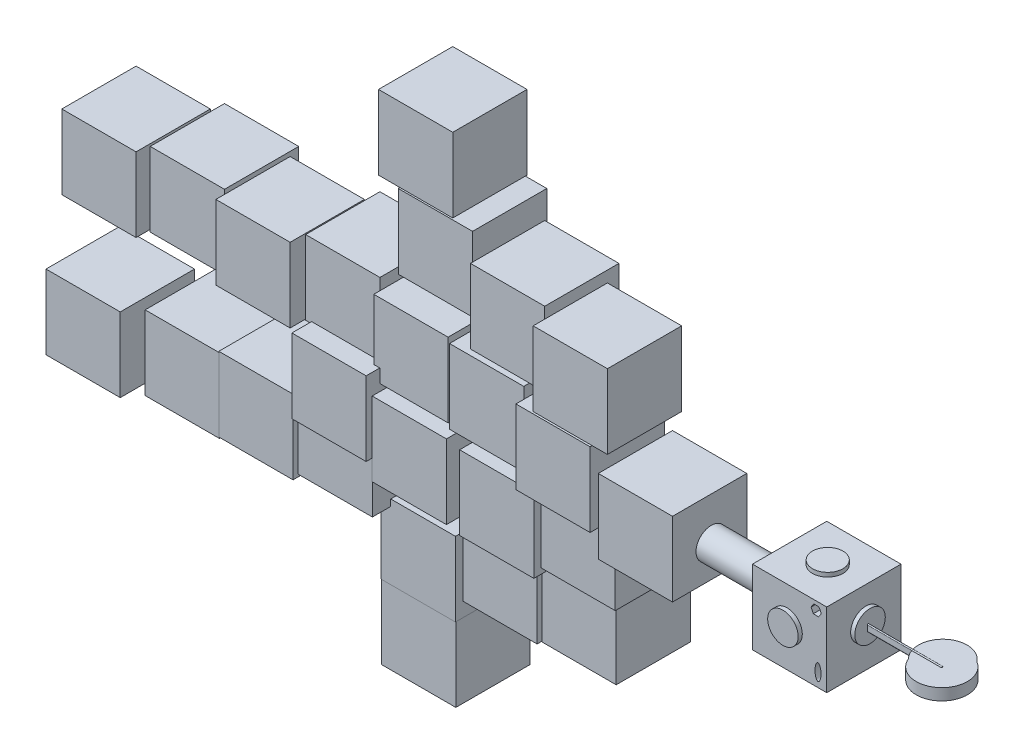
SolidWorks part; units mm, degrees
ref_plane "Front Plane" through (0, 0, 0) normal (0, 0, 1) x (1, 0, 0)
ref_plane "Top Plane" through (0, 0, 0) normal (0, 1, 0) x (1, 0, 0)
ref_plane "Right Plane" through (0, 0, 0) normal (1, 0, 0) x (0, 0, -1)
sketch "Sketch1" plane through (0, 0, 0) normal (0, 0, 1) x (1, 0, 0)
  line L1 (-45, 45) -> (45, 45)
  line L2 (-45, 45) -> (-45, -45)
  line L3 (-45, -45) -> (45, -45)
  line L4 (45, 45) -> (45, -45)
  line L5 (-45, 45) -> (45, -45) construction
  line L6 (-45, -45) -> (45, 45) construction
  point P0 (0, 0)
  dimension "D1" = 90
  dimension "D2" = 90
extrude "Boss-Extrude1" add sketch "Sketch1" along normal blind 90
sketch "Sketch2" plane through (45, 0, 0) normal (1, 0, 0) x (0, 0, -1)
  circle A0 centre (-42.5335, 3.7359) radius 18.4951
extrude "Boss-Extrude2" add sketch "Sketch2" against normal blind 90 and the other way blind 5
sketch "Sketch3" plane through (0, 0, 90) normal (0, 0, 1) x (1, 0, 0)
  circle A0 centre (-3.1268, 1.6243) radius 18.4951
extrude "Boss-Extrude3" add sketch "Sketch3" against normal blind 90 and the other way blind 5
sketch "Sketch4" plane through (0, 45, 0) normal (0, 1, 0) x (0, 0, -1)
  circle A0 centre (-44.963, -1.1407) radius 18.4951
extrude "Boss-Extrude4" add sketch "Sketch4" against normal blind 90 and the other way blind 5
sketch "Sketch5" plane through (-45, 0, 0) normal (-1, 0, 0) x (0, 0, 1)
  circle A0 centre (44.3232, -3.4807) radius 18.4951
extrude "Boss-Extrude5" add sketch "Sketch5" against normal blind 90 and the other way blind 95.6719
sketch "Sketch6" plane through (0, -45, 0) normal (0, -1, 0) x (0, 0, -1)
  circle A0 centre (-43.114, -1.0732) radius 18.4951
extrude "Boss-Extrude6" add sketch "Sketch6" against normal blind 90 and the other way blind 5
sketch "Sketch7" plane through (0, 0, 0) normal (0, 0, -1) x (-1, 0, 0)
  line L1 (-28.8022, 29.8056) -> (-25.9491, 35.3523)
  line L2 (-25.9491, 35.3523) -> (-29.3261, 40.5965)
  line L3 (-29.3261, 40.5965) -> (-35.5562, 40.294)
  line L4 (-35.5562, 40.294) -> (-38.4093, 34.7474)
  line L5 (-38.4093, 34.7474) -> (-35.0323, 29.5031)
  line L6 (-35.0323, 29.5031) -> (-28.8022, 29.8056)
  circle A0 centre (-32.1792, 35.0498) radius 5.4018 construction
extrude "Cut-Extrude1" cut sketch "Sketch7" against normal blind 90
sketch "Sketch8" plane through (0, 0, 90) normal (0, 0, 1) x (1, 0, 0)
  ellipse E0 centre (34.4176, -28.6824) end of major axis (34.4176, -38.4588) minor radius 3.6403
extrude "Cut-Extrude2" cut sketch "Sketch8" against normal blind 90
sketch "Sketch9" plane through (50, 0, 0) normal (1, 0, 0) x (0, 0, -1)
  line L0 (-44.9872, 6.623) -> (-44.9872, 0) construction
  line L1 (-44.0735, 6.623) -> (-44.0735, 0)
  line L2 (-45.9008, 6.623) -> (-45.9008, 0)
  arc A0 (-44.0735, 6.623) -> (-45.9008, 6.623) centre (-44.9872, 6.623) ccw
  arc A1 (-45.9008, 0) -> (-44.0735, 0) centre (-44.9872, 0) ccw
  point P2 (-44.9872, 3.3115)
extrude "Boss-Extrude7" add sketch "Sketch9" along normal blind 90
ref_plane "Plane1" through (140, 6.623, 44.0735) normal (0, 1, 0) x (1, 0, 0)
sketch "Sketch10" plane through (140, 6.623, 44.0735) normal (0, 1, 0) x (1, 0, 0)
  circle A0 centre (-8.4258, 8.1881) radius 29.4355
  circle A1 centre (-0.8539, -0.5784) radius 31.0088
extrude "Boss-Extrude10" add sketch "Sketch10" against normal blind 14 contours A0 | A1
sketch "Sketch11" plane through (-140.6719, 0, 0) normal (-1, 0, 0) x (0, 0, 1)
  line L1 (1.2747, 48.0079) -> (91.2747, 48.0079)
  line L2 (1.2747, 48.0079) -> (1.2747, -41.9921)
  line L3 (1.2747, -41.9921) -> (91.2747, -41.9921)
  line L4 (91.2747, 48.0079) -> (91.2747, -41.9921)
  line L5 (1.2747, 48.0079) -> (91.2747, -41.9921) construction
  line L6 (1.2747, -41.9921) -> (91.2747, 48.0079) construction
  point P0 (46.2747, 3.0079)
  dimension "D1" = 90
  dimension "D2" = 90
extrude "Boss-Extrude11" add sketch "Sketch11" along normal blind 90
sketch "Sketch15" plane through (-230.6719, 0, 0) normal (-1, 0, 0) x (0, 0, 1)
  line L1 (11.1179, 80.8878) -> (101.1179, 80.8878)
  line L2 (11.1179, 80.8878) -> (11.1179, -9.1122)
  line L3 (11.1179, -9.1122) -> (101.1179, -9.1122)
  line L4 (101.1179, 80.8878) -> (101.1179, -9.1122)
  line L5 (11.1179, 80.8878) -> (101.1179, -9.1122) construction
  line L6 (11.1179, -9.1122) -> (101.1179, 80.8878) construction
  point P0 (56.1179, 35.8878)
  dimension "D1" = 90
  dimension "D2" = 90
extrude "Boss-Extrude13" add sketch "Sketch15" along normal blind 90
sketch "Sketch17" plane through (0, -9.1122, 0) normal (0, -1, 0) x (0, 0, 1)
  line L1 (-12.055, 313.464) -> (77.945, 313.464)
  line L2 (-12.055, 313.464) -> (-12.055, 223.464)
  line L3 (-12.055, 223.464) -> (77.945, 223.464)
  line L4 (77.945, 313.464) -> (77.945, 223.464)
  line L5 (-12.055, 313.464) -> (77.945, 223.464) construction
  line L6 (-12.055, 223.464) -> (77.945, 313.464) construction
  point P0 (32.945, 268.464)
  dimension "D1" = 90
  dimension "D2" = 90
extrude "Boss-Extrude15" add sketch "Sketch17" along normal blind 90
sketch "Sketch18" plane through (0, -99.1122, 0) normal (0, -1, 0) x (0, 0, 1)
  line L1 (-24.7948, 325.0184) -> (65.2052, 325.0184)
  line L2 (-24.7948, 325.0184) -> (-24.7948, 235.0184)
  line L3 (-24.7948, 235.0184) -> (65.2052, 235.0184)
  line L4 (65.2052, 325.0184) -> (65.2052, 235.0184)
  line L5 (-24.7948, 325.0184) -> (65.2052, 235.0184) construction
  line L6 (-24.7948, 235.0184) -> (65.2052, 325.0184) construction
  point P0 (20.2052, 280.0184)
  dimension "D1" = 90
  dimension "D2" = 90
extrude "Boss-Extrude16" add sketch "Sketch18" along normal blind 90
sketch "Sketch19" plane through (0, 80.8878, 0) normal (0, 1, 0) x (0, 0, 1)
  line L1 (8.682, -212.1918) -> (98.682, -212.1918)
  line L2 (8.682, -212.1918) -> (8.682, -302.1918)
  line L3 (8.682, -302.1918) -> (98.682, -302.1918)
  line L4 (98.682, -212.1918) -> (98.682, -302.1918)
  line L5 (8.682, -212.1918) -> (98.682, -302.1918) construction
  line L6 (8.682, -302.1918) -> (98.682, -212.1918) construction
  point P0 (53.682, -257.1918)
  dimension "D1" = 90
  dimension "D2" = 90
extrude "Boss-Extrude17" add sketch "Sketch19" along normal blind 90
sketch "Sketch20" plane through (-320.6719, 0, 0) normal (-1, 0, 0) x (0, 0, 1)
  line L1 (1.6043, 94.5759) -> (91.6043, 94.5759)
  line L2 (1.6043, 94.5759) -> (1.6043, 4.5759)
  line L3 (1.6043, 4.5759) -> (91.6043, 4.5759)
  line L4 (91.6043, 94.5759) -> (91.6043, 4.5759)
  line L5 (1.6043, 94.5759) -> (91.6043, 4.5759) construction
  line L6 (1.6043, 4.5759) -> (91.6043, 94.5759) construction
  point P0 (46.6043, 49.5759)
  dimension "D1" = 90
  dimension "D2" = 90
extrude "Boss-Extrude18" add sketch "Sketch20" along normal blind 90
sketch "Sketch21" plane through (-313.464, 0, 0) normal (-1, 0, 0) x (0, 0, 1)
  line L1 (-3.4583, -15.9256) -> (86.5417, -15.9256)
  line L2 (-3.4583, -15.9256) -> (-3.4583, -105.9256)
  line L3 (-3.4583, -105.9256) -> (86.5417, -105.9256)
  line L4 (86.5417, -15.9256) -> (86.5417, -105.9256)
  line L5 (-3.4583, -15.9256) -> (86.5417, -105.9256) construction
  line L6 (-3.4583, -105.9256) -> (86.5417, -15.9256) construction
  point P0 (41.5417, -60.9256)
  dimension "D1" = 90
  dimension "D2" = 90
extrude "Boss-Extrude19" add sketch "Sketch21" along normal blind 90
sketch "Sketch22" plane through (-325.0184, 0, 0) normal (-1, 0, 0) x (0, 0, 1)
  line L1 (-18.9843, -98.3742) -> (71.0157, -98.3742)
  line L2 (-18.9843, -98.3742) -> (-18.9843, -188.3742)
  line L3 (-18.9843, -188.3742) -> (71.0157, -188.3742)
  line L4 (71.0157, -98.3742) -> (71.0157, -188.3742)
  line L5 (-18.9843, -98.3742) -> (71.0157, -188.3742) construction
  line L6 (-18.9843, -188.3742) -> (71.0157, -98.3742) construction
  point P0 (26.0157, -143.3742)
  dimension "D1" = 90
  dimension "D2" = 90
extrude "Boss-Extrude20" add sketch "Sketch22" along normal blind 90
sketch "Sketch23" plane through (-410.6719, 0, 0) normal (-1, 0, 0) x (0, 0, 1)
  line L1 (3.361, 102.1077) -> (93.361, 102.1077)
  line L2 (3.361, 102.1077) -> (3.361, 12.1077)
  line L3 (3.361, 12.1077) -> (93.361, 12.1077)
  line L4 (93.361, 102.1077) -> (93.361, 12.1077)
  line L5 (3.361, 102.1077) -> (93.361, 12.1077) construction
  line L6 (3.361, 12.1077) -> (93.361, 102.1077) construction
  point P0 (48.361, 57.1077)
  dimension "D1" = 90
  dimension "D2" = 90
extrude "Boss-Extrude21" add sketch "Sketch23" along normal blind 90
sketch "Sketch24" plane through (-403.464, 0, 0) normal (-1, 0, 0) x (0, 0, 1)
  line L1 (12.5578, 3.5082) -> (102.5578, 3.5082)
  line L2 (12.5578, 3.5082) -> (12.5578, -86.4918)
  line L3 (12.5578, -86.4918) -> (102.5578, -86.4918)
  line L4 (102.5578, 3.5082) -> (102.5578, -86.4918)
  line L5 (12.5578, 3.5082) -> (102.5578, -86.4918) construction
  line L6 (12.5578, -86.4918) -> (102.5578, 3.5082) construction
  point P0 (57.5578, -41.4918)
  dimension "D1" = 90
  dimension "D2" = 90
extrude "Boss-Extrude22" add sketch "Sketch24" along normal blind 90
sketch "Sketch25" plane through (-302.1918, 0, 0) normal (-1, 0, 0) x (0, 0, 1)
  line L1 (-5.3051, 184.4714) -> (84.6949, 184.4714)
  line L2 (-5.3051, 184.4714) -> (-5.3051, 94.4714)
  line L3 (-5.3051, 94.4714) -> (84.6949, 94.4714)
  line L4 (84.6949, 184.4714) -> (84.6949, 94.4714)
  line L5 (-5.3051, 184.4714) -> (84.6949, 94.4714) construction
  line L6 (-5.3051, 94.4714) -> (84.6949, 184.4714) construction
  point P0 (39.6949, 139.4714)
  dimension "D1" = 90
  dimension "D2" = 90
extrude "Boss-Extrude23" add sketch "Sketch25" along normal blind 90
sketch "Sketch26" plane through (-415.0184, 0, 0) normal (-1, 0, 0) x (0, 0, 1)
  line L1 (-9.9198, -115.776) -> (80.0802, -115.776)
  line L2 (-9.9198, -115.776) -> (-9.9198, -205.776)
  line L3 (-9.9198, -205.776) -> (80.0802, -205.776)
  line L4 (80.0802, -115.776) -> (80.0802, -205.776)
  line L5 (-9.9198, -115.776) -> (80.0802, -205.776) construction
  line L6 (-9.9198, -205.776) -> (80.0802, -115.776) construction
  point P0 (35.0802, -160.776)
  dimension "D1" = 90
  dimension "D2" = 90
extrude "Boss-Extrude24" add sketch "Sketch26" along normal blind 90
sketch "Sketch27" plane through (-493.464, 0, 0) normal (-1, 0, 0) x (0, 0, 1)
  line L1 (19.8591, 28.3632) -> (109.8591, 28.3632)
  line L2 (19.8591, 28.3632) -> (19.8591, -61.6368)
  line L3 (19.8591, -61.6368) -> (109.8591, -61.6368)
  line L4 (109.8591, 28.3632) -> (109.8591, -61.6368)
  line L5 (19.8591, 28.3632) -> (109.8591, -61.6368) construction
  line L6 (19.8591, -61.6368) -> (109.8591, 28.3632) construction
  point P0 (64.8591, -16.6368)
  dimension "D1" = 90
  dimension "D2" = 90
extrude "Boss-Extrude25" add sketch "Sketch27" along normal blind 90
sketch "Sketch28" plane through (-500.6719, 0, 0) normal (-1, 0, 0) x (0, 0, 1)
  line L1 (-4.0373, 116.1038) -> (85.9627, 116.1038)
  line L2 (-4.0373, 116.1038) -> (-4.0373, 26.1038)
  line L3 (-4.0373, 26.1038) -> (85.9627, 26.1038)
  line L4 (85.9627, 116.1038) -> (85.9627, 26.1038)
  line L5 (-4.0373, 116.1038) -> (85.9627, 26.1038) construction
  line L6 (-4.0373, 26.1038) -> (85.9627, 116.1038) construction
  point P0 (40.9627, 71.1038)
  dimension "D1" = 90
  dimension "D2" = 90
extrude "Boss-Extrude26" add sketch "Sketch28" along normal blind 90
sketch "Sketch29" plane through (-590.6719, 0, 0) normal (-1, 0, 0) x (0, 0, 1)
  line L1 (14.7968, 117.4361) -> (104.7968, 117.4361)
  line L2 (14.7968, 117.4361) -> (14.7968, 27.4361)
  line L3 (14.7968, 27.4361) -> (104.7968, 27.4361)
  line L4 (104.7968, 117.4361) -> (104.7968, 27.4361)
  line L5 (14.7968, 117.4361) -> (104.7968, 27.4361) construction
  line L6 (14.7968, 27.4361) -> (104.7968, 117.4361) construction
  point P0 (59.7968, 72.4361)
  dimension "D1" = 90
  dimension "D2" = 90
extrude "Boss-Extrude27" add sketch "Sketch29" along normal blind 90
sketch "Sketch30" plane through (-493.464, 0, 0) normal (-1, 0, 0) x (0, 0, 1)
  line L1 (12.2929, -33.6708) -> (102.2929, -33.6708)
  line L2 (12.2929, -33.6708) -> (12.2929, -123.6708)
  line L3 (12.2929, -123.6708) -> (102.2929, -123.6708)
  line L4 (102.2929, -33.6708) -> (102.2929, -123.6708)
  line L5 (12.2929, -33.6708) -> (102.2929, -123.6708) construction
  line L6 (12.2929, -123.6708) -> (102.2929, -33.6708) construction
  point P0 (57.2929, -78.6708)
  dimension "D1" = 90
  dimension "D2" = 90
extrude "Boss-Extrude28" add sketch "Sketch30" along normal blind 90
sketch "Sketch31" plane through (-583.464, 0, 0) normal (-1, 0, 0) x (0, 0, 1)
  line L1 (18.4515, -36.5708) -> (108.4515, -36.5708)
  line L2 (18.4515, -36.5708) -> (18.4515, -126.5708)
  line L3 (18.4515, -126.5708) -> (108.4515, -126.5708)
  line L4 (108.4515, -36.5708) -> (108.4515, -126.5708)
  line L5 (18.4515, -36.5708) -> (108.4515, -126.5708) construction
  line L6 (18.4515, -126.5708) -> (108.4515, -36.5708) construction
  point P0 (63.4515, -81.5708)
  dimension "D1" = 90
  dimension "D2" = 90
extrude "Boss-Extrude29" add sketch "Sketch31" along normal blind 90
sketch "Sketch32" plane through (-680.6719, 0, 0) normal (-1, 0, 0) x (0, 0, 1)
  line L1 (4.3827, 122.8494) -> (94.3827, 122.8494)
  line L2 (4.3827, 122.8494) -> (4.3827, 32.8494)
  line L3 (4.3827, 32.8494) -> (94.3827, 32.8494)
  line L4 (94.3827, 122.8494) -> (94.3827, 32.8494)
  line L5 (4.3827, 122.8494) -> (94.3827, 32.8494) construction
  line L6 (4.3827, 32.8494) -> (94.3827, 122.8494) construction
  point P0 (49.3827, 77.8494)
  dimension "D1" = 90
  dimension "D2" = 90
extrude "Boss-Extrude30" add sketch "Sketch32" along normal blind 90
sketch "Sketch33" plane through (-673.464, 0, 0) normal (-1, 0, 0) x (0, 0, 1)
  line L1 (17.7306, -38.4399) -> (107.7306, -38.4399)
  line L2 (17.7306, -38.4399) -> (17.7306, -128.4399)
  line L3 (17.7306, -128.4399) -> (107.7306, -128.4399)
  line L4 (107.7306, -38.4399) -> (107.7306, -128.4399)
  line L5 (17.7306, -38.4399) -> (107.7306, -128.4399) construction
  line L6 (17.7306, -128.4399) -> (107.7306, -38.4399) construction
  point P0 (62.7306, -83.4399)
  dimension "D1" = 90
  dimension "D2" = 90
extrude "Boss-Extrude31" add sketch "Sketch33" along normal blind 90
sketch "Sketch34" plane through (-770.6719, 0, 0) normal (-1, 0, 0) x (0, 0, 1)
  line L1 (21.536, 125.74) -> (111.536, 125.74)
  line L2 (21.536, 125.74) -> (21.536, 35.74)
  line L3 (21.536, 35.74) -> (111.536, 35.74)
  line L4 (111.536, 125.74) -> (111.536, 35.74)
  line L5 (21.536, 125.74) -> (111.536, 35.74) construction
  line L6 (21.536, 35.74) -> (111.536, 125.74) construction
  point P0 (66.536, 80.74)
  dimension "D1" = 90
  dimension "D2" = 90
extrude "Boss-Extrude32" add sketch "Sketch34" along normal blind 90
sketch "Sketch35" plane through (-763.464, 0, 0) normal (-1, 0, 0) x (0, 0, 1)
  line L1 (47.929, -25.5038) -> (137.929, -25.5038)
  line L2 (47.929, -25.5038) -> (47.929, -115.5038)
  line L3 (47.929, -115.5038) -> (137.929, -115.5038)
  line L4 (137.929, -25.5038) -> (137.929, -115.5038)
  line L5 (47.929, -25.5038) -> (137.929, -115.5038) construction
  line L6 (47.929, -115.5038) -> (137.929, -25.5038) construction
  point P0 (92.929, -70.5038)
  dimension "D1" = 90
  dimension "D2" = 90
extrude "Boss-Extrude33" add sketch "Sketch35" along normal blind 90
sketch "Sketch36" plane through (0, -205.776, 0) normal (0, -1, 0) x (0, 0, 1)
  line L1 (-10.4988, 505.1159) -> (79.5012, 505.1159)
  line L2 (-10.4988, 505.1159) -> (-10.4988, 415.1159)
  line L3 (-10.4988, 415.1159) -> (79.5012, 415.1159)
  line L4 (79.5012, 505.1159) -> (79.5012, 415.1159)
  line L5 (-10.4988, 505.1159) -> (79.5012, 415.1159) construction
  line L6 (-10.4988, 415.1159) -> (79.5012, 505.1159) construction
  point P0 (34.5012, 460.1159)
  dimension "D1" = 90
  dimension "D2" = 90
extrude "Boss-Extrude34" add sketch "Sketch36" along normal blind 90
sketch "Sketch37" plane through (-392.1918, 0, 0) normal (-1, 0, 0) x (0, 0, 1)
  line L1 (-7.8464, 216.8122) -> (82.1536, 216.8122)
  line L2 (-7.8464, 216.8122) -> (-7.8464, 126.8122)
  line L3 (-7.8464, 126.8122) -> (82.1536, 126.8122)
  line L4 (82.1536, 216.8122) -> (82.1536, 126.8122)
  line L5 (-7.8464, 216.8122) -> (82.1536, 126.8122) construction
  line L6 (-7.8464, 126.8122) -> (82.1536, 216.8122) construction
  point P0 (37.1536, 171.8122)
  dimension "D1" = 90
  dimension "D2" = 90
extrude "Boss-Extrude35" add sketch "Sketch37" along normal blind 90
sketch "Sketch38" plane through (0, 216.8122, 0) normal (0, 1, 0) x (0, 0, 1)
  line L1 (-9.8545, -418.1939) -> (80.1455, -418.1939)
  line L2 (-9.8545, -418.1939) -> (-9.8545, -508.1939)
  line L3 (-9.8545, -508.1939) -> (80.1455, -508.1939)
  line L4 (80.1455, -418.1939) -> (80.1455, -508.1939)
  line L5 (-9.8545, -418.1939) -> (80.1455, -508.1939) construction
  line L6 (-9.8545, -508.1939) -> (80.1455, -418.1939) construction
  point P0 (35.1455, -463.1939)
  dimension "D1" = 90
  dimension "D2" = 90
extrude "Boss-Extrude36" add sketch "Sketch38" along normal blind 90
